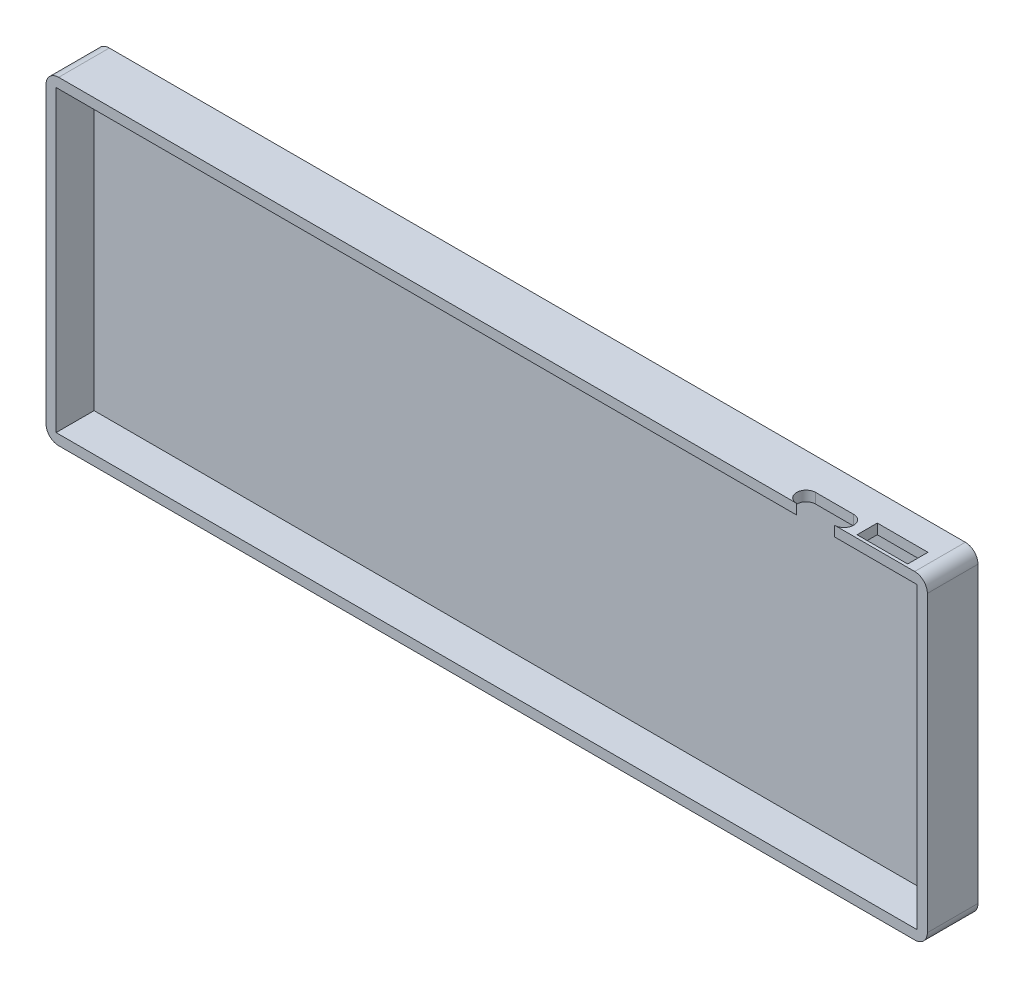
SolidWorks part; units mm, degrees
ref_plane "Front Plane" through (0, 0, 0) normal (0, 0, 1) x (1, 0, 0)
ref_plane "Top Plane" through (0, 0, 0) normal (0, 1, 0) x (1, 0, 0)
ref_plane "Right Plane" through (0, 0, 0) normal (1, 0, 0) x (0, 0, -1)
sketch "Sketch1" plane through (0, 0, 0) normal (0, 0, 1) x (1, 0, 0)
  line L1 (174, 63) -> (-174, 63)
  line L2 (174, 63) -> (174, -63)
  line L3 (174, -63) -> (-174, -63)
  line L4 (-174, 63) -> (-174, -63)
  line L5 (174, 63) -> (-174, -63) construction
  line L6 (174, -63) -> (-174, 63) construction
  point P0 (0, 0)
  dimension "D1" = 348
  dimension "D2" = 126
extrude "Boss-Extrude1" add sketch "Sketch1" along normal blind 20
sketch "Sketch2" plane through (0, 0, 20) normal (0, 0, 1) x (1, 0, 0)
  line L1 (170, 59) -> (-170, 59)
  line L2 (170, 59) -> (170, -59)
  line L3 (170, -59) -> (-170, -59)
  line L4 (-170, 59) -> (-170, -59)
  line L5 (170, 59) -> (-170, -59) construction
  line L6 (170, -59) -> (-170, 59) construction
  point P0 (0, 0)
  dimension "D1" = 340
  dimension "D2" = 118
extrude "Cut-Extrude1" cut sketch "Sketch2" against normal blind 15
sketch "Sketch4" plane through (0, 63, 0) normal (0, 1, 0) x (1, 0, 0)
  line L0 (122.39, -16.25) -> (137.39, -16.25) construction
  line L1 (122.39, -12.5) -> (137.39, -12.5)
  line L2 (122.39, -20) -> (137.39, -20)
  line L3 (174, -20) -> (174, 0) construction
  line L4 (174, -20) -> (-174, -20) construction
  arc A0 (122.39, -12.5) -> (122.39, -20) centre (122.39, -16.25) ccw
  arc A1 (137.39, -20) -> (137.39, -12.5) centre (137.39, -16.25) ccw
  point P2 (129.89, -16.25)
  dimension "D1" = 36.61
  dimension "D3" = 15
  dimension "D2" = 0
  dimension "D4" = 7.5
extrude "Cut-Extrude2" cut sketch "Sketch4" against normal up to next contours L2 A1 L1 A0
sketch "Sketch5" plane through (0, 63, 0) normal (0, 1, 0) x (1, 0, 0)
  line L0 (174, -20) -> (174, 0) construction
  line L1 (145.05, -10.81) -> (165.05, -10.81)
  line L2 (145.05, -10.81) -> (145.05, -18.81)
  line L3 (145.05, -18.81) -> (165.05, -18.81)
  line L4 (165.05, -10.81) -> (165.05, -18.81)
  line L6 (174, -20) -> (137.39, -20) construction
  dimension "D1" = 8.95
  dimension "D3" = 1.19
  dimension "D4" = 8
  dimension "D5" = 20
extrude "Cut-Extrude3" cut sketch "Sketch5" against normal up to next
fillet "Fillet1" radius 5 4 edges at (-174, 63, 10) (-174, -63, 10) (174, -63, 10) (174, 63, 10)
